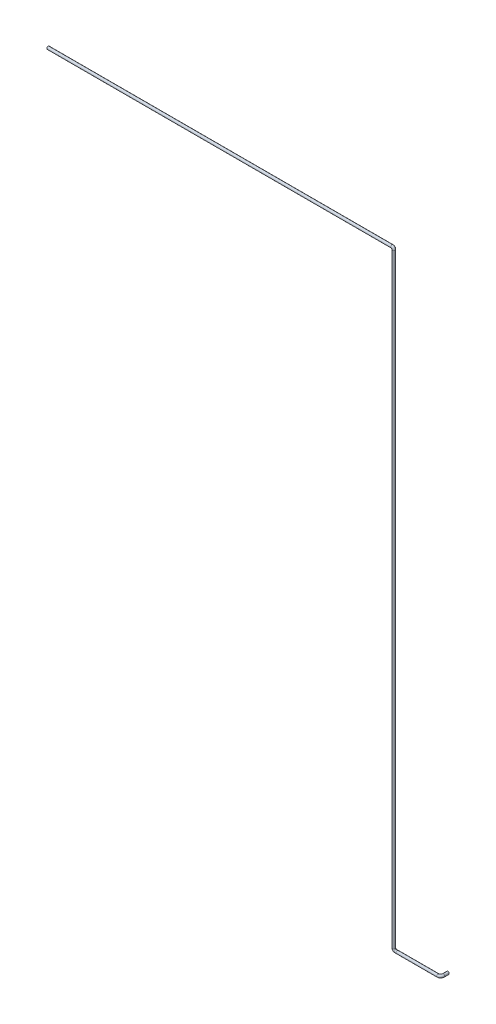
SolidWorks part; units mm, degrees
material "Copper"
ref_plane "Front" through (0, 0, 0) normal (0, 0, 1) x (1, 0, 0)
ref_plane "Top" through (0, 0, 0) normal (0, 1, 0) x (1, 0, 0)
ref_plane "Right" through (0, 0, 0) normal (1, 0, 0) x (0, 0, -1)
sketch "Sketch1" plane through (0, 0, 0) normal (0, 0, 1) x (1, 0, 0)
  line L0 (0, -6.985) -> (0, -9.525) construction
  circle A0 centre (0, 0) radius 9.525
  circle A1 centre (0, 0) radius 6.985
  dimension "D1" = 19.05
  dimension "D2" = 2.54
sketch "Sketch2" plane through (0, 0, 0) normal (0, 1, 0) x (1, 0, 0)
  line L0 (0, 0) -> (0, -31.75)
  line L1 (-19.05, -50.8) -> (-304.8, -50.8)
  arc A0 (-19.05, -50.8) -> (0, -31.75) centre (-19.05, -31.75) ccw
  point P6 (0, -50.8)
  dimension "D3" = 19.05
  dimension "D1" = 50.8
  dimension "D2" = 304.8
ref_plane "Plane1" through (0, 0, 50.8) normal (0, 0, -1) x (-1, 0, 0)
sketch "Sketch3" plane through (0, 0, 50.8) normal (0, 0, -1) x (-1, 0, 0)
  line L0 (304.8, 0) -> (317.5, 0)
  line L1 (19.05, 0) -> (304.8, 0) construction
  line L2 (330.2, 12.7) -> (330.2, 4279.9)
  line L3 (342.9, 4292.6) -> (2768.6, 4292.6)
  arc A0 (330.2, 12.7) -> (317.5, 0) centre (317.5, 12.7) cw
  arc A1 (342.9, 4292.6) -> (330.2, 4279.9) centre (342.9, 4279.9) ccw
  point P11 (330.2, 4292.6)
  dimension "D1" = 12.7
  dimension "D4" = 12.7
  dimension "D2" = 12.7
  dimension "D3" = 2438.4
  dimension "D5" = 4292.6
curve "CompCurve1"
sweep "Sweep1" add profiles "Sketch1" path "CompCurve1"
